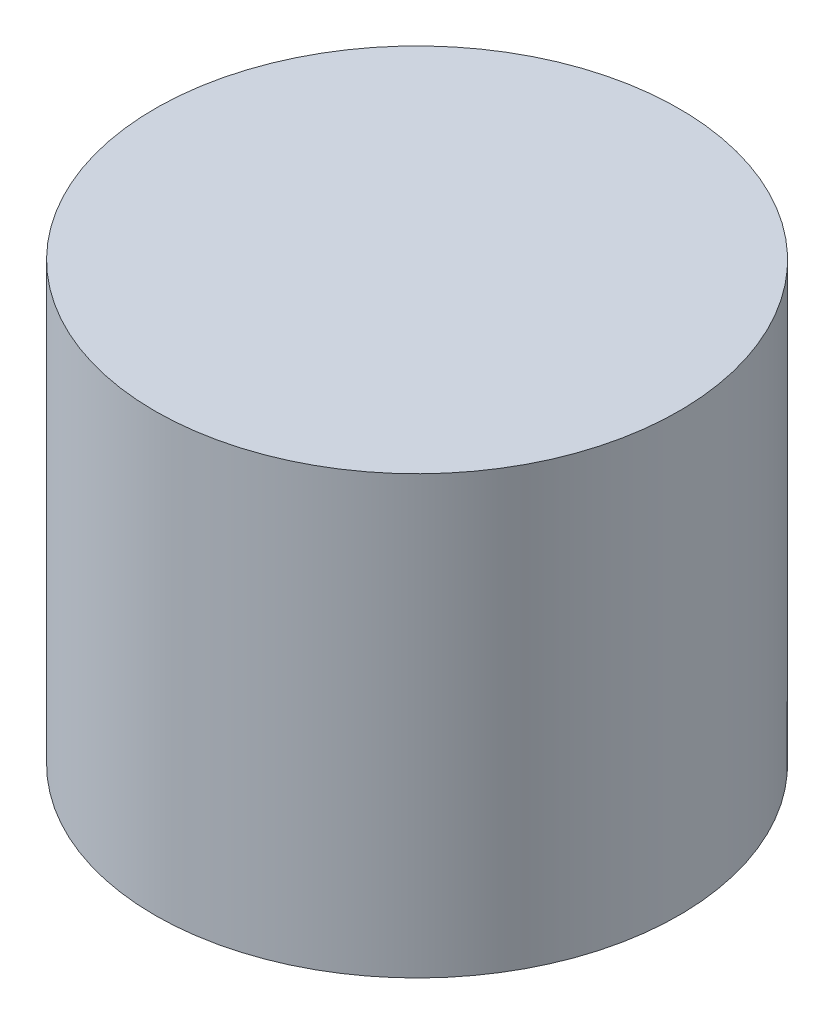
SolidWorks part; units mm, degrees
ref_plane "Front Plane" through (0, 0, 0) normal (0, 0, 1) x (1, 0, 0)
ref_plane "Top Plane" through (0, 0, 0) normal (0, 1, 0) x (1, 0, 0)
ref_plane "Right Plane" through (0, 0, 0) normal (1, 0, 0) x (0, 0, -1)
sketch "Sketch1" plane through (0, 0, 0) normal (0, 1, 0) x (1, 0, 0)
  circle A0 centre (0, 0) radius 6
  dimension "D1" = 12
extrude "Boss-Extrude1" add sketch "Sketch1" along normal blind 10
sketch "Sketch2" plane through (0, 0, 0) normal (0, -1, 0) x (1, 0, 0)
  circle A0 centre (0, 0) radius 1
  dimension "D1" = 2
extrude "Cut-Extrude1" cut sketch "Sketch2" against normal blind 2
